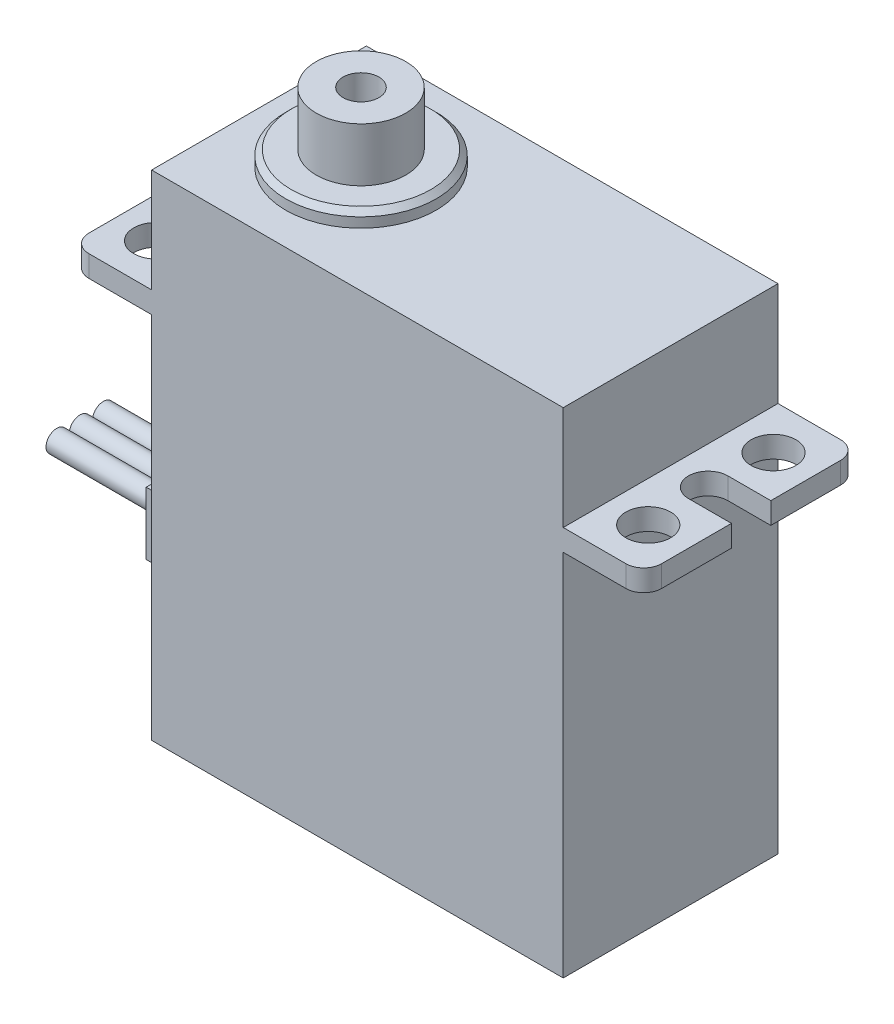
SolidWorks part; units mm, degrees
ref_plane "Front Plane" through (0, 0, 0) normal (0, 0, 1) x (1, 0, 0)
ref_plane "Top Plane" through (0, 0, 0) normal (0, 1, 0) x (1, 0, 0)
ref_plane "Right Plane" through (0, 0, 0) normal (1, 0, 0) x (0, 0, -1)
sketch "Эскиз1" plane through (0, 0, 0) normal (0, 0, 1) x (1, 0, 0)
  line L0 (0, 5.0732) -> (0, -2.902) construction
  line L1 (-11.5, -13.8) -> (11.5, -13.8)
  line L2 (-11.5, -13.8) -> (-11.5, 13.8)
  line L3 (-11.5, 13.8) -> (11.5, 13.8)
  line L4 (11.5, -13.8) -> (11.5, 13.8)
  line L5 (-11.5, -13.8) -> (11.5, 13.8) construction
  line L6 (-11.5, 13.8) -> (11.5, -13.8) construction
  line L7 (-16, 6.8) -> (-11.5, 6.8)
  line L8 (-16, 6.8) -> (-16, 8)
  line L9 (-16, 8) -> (-11.5, 8)
  line L10 (-11.5, 6.8) -> (-11.5, 8)
  line L11 (-16, 6.8) -> (-11.5, 8) construction
  line L12 (-16, 8) -> (-11.5, 6.8) construction
  line L13 (16, 8) -> (11.5, 8)
  line L14 (11.5, 6.8) -> (11.5, 8)
  line L15 (16, 6.8) -> (11.5, 6.8)
  line L16 (16, 6.8) -> (16, 8)
  point P0 (0, 0)
  point P5 (-13.75, 7.4)
  dimension "D1" = 23
  dimension "D2" = 27.6
  dimension "D3" = 20.6
  dimension "D4" = 1.2
  dimension "D5" = 32
extrude "Бобышка-Вытянуть1" add sketch "Эскиз1" along normal mid plane 12 contours L1 L4 L3 L2 | L9 L8 L7 L2 | L15 L16 L13 L4
sketch "Эскиз2" plane through (0, 13.8, 0) normal (0, 1, 0) x (1, 0, 0)
  line L0 (-11.5, 0) -> (11.5, 0) construction
  line L1 (-11.5, -6) -> (-11.5, 6) construction
  line L2 (11.5, -6) -> (11.5, 6) construction
  line L3 (-11.5, -6) -> (-11.5, 6) construction
  circle A0 centre (-5.8, 0) radius 4.2
  point P8 (-6.1166, 0)
  dimension "D1" = 8.4
  dimension "D2" = 1.5
extrude "Бобышка-Вытянуть2" add sketch "Эскиз2" along normal blind 0.85
chamfer "Фаска1" distance 0.3 angle 45 1 edges at (-5.8, 14.65, 4.2)
sketch "Эскиз4" plane through (0, 14.65, 0) normal (0, 1, 0) x (1, 0, 0)
  circle A0 centre (-5.8, 0) radius 2.5
  circle A1 centre (-5.8, 0) radius 3.9
  circle A2 centre (-5.8, 0) radius 3.9 construction
  circle A3 centre (-5.8, 0) radius 1
  dimension "D2" = 5
  dimension "D3" = 2
  dimension "D1" = 0
extrude "Бобышка-Вытянуть3" add sketch "Эскиз4" along normal blind 3
sketch "Эскиз3" plane through (0, 8, 0) normal (0, 1, 0) x (1, 0, 0)
  line L0 (-13.75, 6) -> (-13.75, -6) construction
  line L1 (-16, 6) -> (-11.5, 6) construction
  line L2 (-16, -6) -> (-11.5, -6) construction
  line L3 (0, -6) -> (0, 6) construction
  line L4 (-11.5, -6) -> (11.5, -6) construction
  line L5 (-11.5, 6) -> (11.5, 6) construction
  line L6 (-16, 0) -> (16, 0) construction
  line L7 (-16, -6) -> (-16, 6) construction
  line L8 (16, -6) -> (16, 6) construction
  line L9 (-16, 1.1) -> (-13.6, 1.1)
  line L10 (-13.6, -1.1) -> (-16, -1.1)
  line L11 (-12.5, 4.2867) -> (-12.5, 2.4321) construction
  line L12 (-16, 1.1) -> (-16, -1.1)
  line L13 (16, 1.1) -> (13.6, 1.1)
  line L14 (13.6, -1.1) -> (16, -1.1)
  line L15 (16, 1.1) -> (16, -1.1)
  circle A0 centre (-13.75, 3.5) radius 1.25
  circle A1 centre (-13.75, -3.5) radius 1.25
  circle A2 centre (13.75, -3.5) radius 1.25
  circle A3 centre (13.75, 3.5) radius 1.25
  arc A4 (-13.6, 1.1) -> (-13.6, -1.1) centre (-13.6, 0) cw
  arc A5 (13.6, 1.1) -> (13.6, -1.1) centre (13.6, 0) ccw
  dimension "D1" = 2.5
  dimension "D2" = 7
  dimension "D3" = 12
  dimension "D4" = 2.5
  dimension "D5" = 2.2
  dimension "D6" = 1.1
extrude "Вырез-Вытянуть1" cut sketch "Эскиз3" against normal through all both and the other way through all
fillet "Скругление1" radius 1 4 edges at (-16, 7.4, -6) (16, 7.4, -6) (16, 7.4, 6) (-16, 7.4, 6)
sketch "Эскиз5" plane through (-11.5, 0, 0) normal (-1, 0, 0) x (0, 0, 1)
  line L0 (0, -13.8) -> (0, 0) construction
  line L1 (6, -13.8) -> (-6, -13.8) construction
  line L2 (-6, -6.65) -> (6, -6.65) construction
  line L3 (-6, -13.8) -> (-6, 6.8) construction
  line L4 (6, -13.8) -> (6, 6.8) construction
  line L6 (-2.8, -8.4) -> (2.8, -8.4)
  line L7 (-2.8, -8.4) -> (-2.8, -4.9)
  line L8 (-2.8, -4.9) -> (2.8, -4.9)
  line L9 (2.8, -8.4) -> (2.8, -4.9)
  line L10 (-2.8, -8.4) -> (2.8, -4.9) construction
  line L11 (-2.8, -4.9) -> (2.8, -8.4) construction
  point P11 (0, -6.65)
  point P16 (0, 0)
  point P17 (0, 0)
  point P18 (0, 0)
  point P19 (0, 0)
  point P20 (0, 0)
  point P21 (2.5583, -4.9)
  dimension "D1" = 5.4
  dimension "D2" = 3.5
  dimension "D3" = 5.6
extrude "Бобышка-Вытянуть4" add sketch "Эскиз5" along normal blind 3.5
sketch "Эскиз6" plane through (-15, 0, 0) normal (-1, 0, 0) x (0, 0, 1)
  line L0 (-2.8, -6.65) -> (2.8, -6.65) construction
  line L1 (0, -4.9) -> (0, -8.4) construction
  line L4 (2.8, -8.4) -> (2.8, -4.9)
  line L5 (2.8, -4.9) -> (-2.8, -4.9)
  line L6 (-2.8, -4.9) -> (-2.8, -8.4)
  line L7 (-2.8, -8.4) -> (2.8, -8.4)
  line L8 (2.8, -8.4) -> (2.8, -4.9) construction
  line L9 (2.8, -4.9) -> (-2.8, -4.9) construction
  line L10 (-2.8, -4.9) -> (-2.8, -8.4) construction
  line L11 (-2.8, -8.4) -> (2.8, -8.4) construction
  circle A0 centre (0, -6.65) radius 0.6
  circle A1 centre (1.3, -6.65) radius 0.6
  circle A2 centre (-1.3, -6.65) radius 0.6
  dimension "D2" = 1.2
  dimension "D3" = 0.1
  dimension "D4" = 0.1
  dimension "D1" = 0
extrude "Бобышка-Вытянуть7" add sketch "Эскиз6" along normal blind 6.5
equation "\"D4@Эскиз3\"=\"D3@Эскиз3\"/2 - \"D2@Эскиз3\"/2"
equation "\"D6@Эскиз3\"=\"D5@Эскиз3\"/2"
